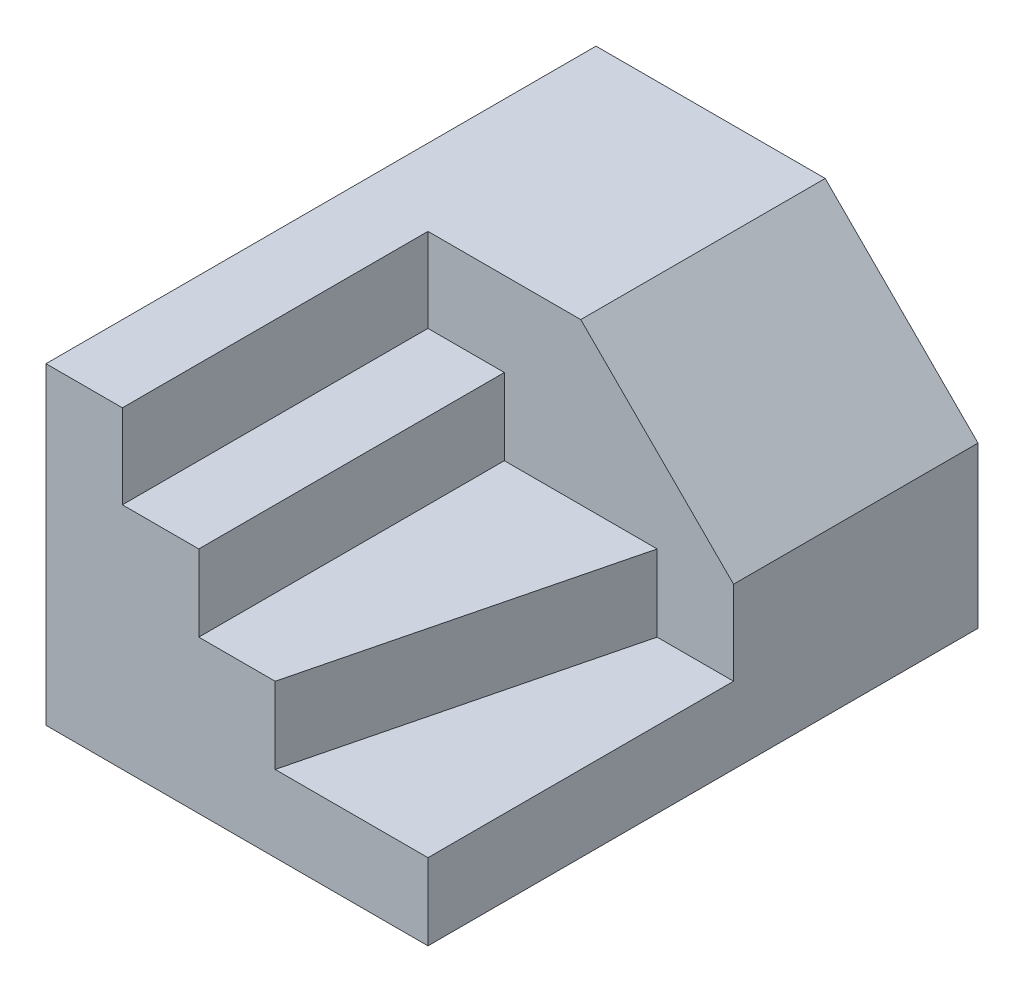
SolidWorks part; units mm, degrees
ref_plane "Front Plane" through (0, 0, 0) normal (0, 0, 1) x (1, 0, 0)
ref_plane "Top Plane" through (0, 0, 0) normal (0, 1, 0) x (1, 0, 0)
ref_plane "Right Plane" through (0, 0, 0) normal (1, 0, 0) x (0, 0, -1)
sketch "Sketch1" plane through (0, 0, 0) normal (0, 1, 0) x (1, 0, 0)
  line L1 (0, 0) -> (1270, 0)
  line L2 (0, 0) -> (0, 1828.8)
  line L3 (0, 1828.8) -> (1270, 1828.8)
  line L4 (1270, 0) -> (1270, 1828.8)
  dimension "D1" = 1828.8
  dimension "D2" = 1270
extrude "Boss-Extrude1" add sketch "Sketch1" along normal blind 254
sketch "Sketch2" plane through (0, 0, -1828.8) normal (0, 0, -1) x (-1, 0, 0)
  line L0 (-1270, 254) -> (-1270, 533.4)
  line L1 (-1270, 533.4) -> (-762, 1041.4)
  line L2 (-762, 1041.4) -> (0, 1041.4)
  line L3 (0, 1041.4) -> (0, 254)
  line L4 (0, 254) -> (-1270, 254)
  point P7 (0, 0)
  point P8 (0, 0)
  point P10 (-1252.7239, 520.0294)
  point P11 (-596.4991, 708.335)
  point P12 (-1270, 533.4)
  point P13 (-1270, 533.4)
  dimension "D1" = 787.4
  dimension "D2" = 508
  dimension "D3" = 45
extrude "Boss-Extrude2" add sketch "Sketch2" against normal blind 812.8
sketch "Sketch3" plane through (0, 254, 0) normal (0, 1, 0) x (1, 0, 0)
  line L0 (1270, 1016) -> (0, 1016) construction
  line L1 (0, 0) -> (254, 0)
  line L2 (0, 0) -> (0, 1016)
  line L3 (0, 1016) -> (254, 1016)
  line L4 (254, 0) -> (254, 1016)
  point P7 (254, 0)
  dimension "D1" = 254
extrude "Boss-Extrude4" add sketch "Sketch3" along normal blind 787.4
sketch "Sketch6" plane through (254, 0, 0) normal (1, 0, 0) x (0, 0, -1)
  line L0 (1016, 1041.4) -> (1016, 254) construction
  line L1 (0, 254) -> (1016, 254)
  line L2 (0, 254) -> (0, 762)
  line L3 (0, 762) -> (1016, 762)
  line L4 (1016, 254) -> (1016, 762)
  dimension "D1" = 508
extrude "Boss-Extrude5" add sketch "Sketch6" along normal blind 254
sketch "Sketch7" plane through (0, 254, 0) normal (0, 1, 0) x (1, 0, 0)
  line L0 (508, 1016) -> (1016, 1016)
  line L1 (1270, 1016) -> (508, 1016) construction
  line L2 (1016, 1016) -> (762, 0)
  line L3 (508, 0) -> (1270, 0) construction
  line L4 (762, 0) -> (508, 0)
  line L5 (508, 0) -> (508, 1016)
  dimension "D1" = 254
  dimension "D2" = 508
extrude "Boss-Extrude6" add sketch "Sketch7" along normal blind 254
